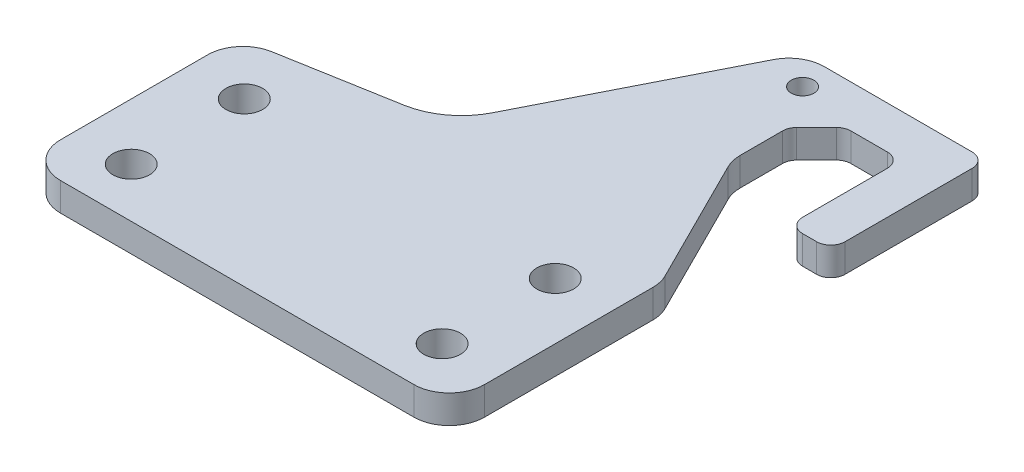
SolidWorks part; units mm, degrees
material "Thornel Mat VMA"
ref_plane "Front" through (0, 0, 0) normal (0, 0, 1) x (1, 0, 0)
ref_plane "Top" through (0, 0, 0) normal (0, 1, 0) x (1, 0, 0)
ref_plane "Right" through (0, 0, 0) normal (1, 0, 0) x (0, 0, -1)
sketch "草图1" plane through (0, 0, 0) normal (0, 1, 0) x (1, 0, 0)
  line L0 (0, 0) -> (0, 59.5856) construction
  line L1 (-30, -15) -> (30, -15)
  line L2 (-30, -15) -> (-30, 15)
  line L4 (30, -15) -> (30, 15)
  line L5 (-30, -15) -> (30, 15) construction
  line L6 (-30, 15) -> (30, -15) construction
  line L7 (30, 15) -> (20, 35)
  line L8 (20, 35) -> (20, 43)
  line L9 (20, 43) -> (24, 47)
  line L10 (24, 47) -> (24, 53)
  line L11 (24, 53) -> (12, 53)
  line L13 (12, 53) -> (-5, 19.4082)
  line L14 (-5, 19.4082) -> (-30, 15)
  point P0 (0, 0)
  dimension "D1" = 30
  dimension "D2" = 60
  dimension "D3" = 20
  dimension "D4" = 8
  dimension "D5" = 8
  dimension "D6" = 4
  dimension "D7" = 135
  dimension "D8" = 20
  dimension "D9" = 6
  dimension "D10" = 100
  dimension "D11" = 25
extrude "凸台-拉伸1" add sketch "草图1" along normal blind 4
fillet "圆角1" radius 10 1 edges at (-5, 2, -19.4082)
fillet "圆角2" radius 5 6 edges at (12, 2, -53) (20, 2, -35) (30, 2, -15) (30, 2, 15) (-30, 2, 15) (-30, 2, -15)
sketch "草图2" plane through (0, 4, 0) normal (0, 1, 0) x (1, 0, 0)
  line L0 (-30, 10.8045) -> (-30, -10) construction
  line L1 (-25, -15) -> (25, -15) construction
  line L2 (0, 0) -> (0, 22.3735) construction
  line L4 (0, 0) -> (-17.4119, 0) construction
  circle A0 centre (-22, 8) radius 2.6
  circle A1 centre (22, 8) radius 2.6
  circle A2 centre (22, -8) radius 2.6
  circle A3 centre (-22, -8) radius 2.6
  dimension "D1" = 5.2
  dimension "D2" = 8
  dimension "D3" = 23
extrude "切除-拉伸1" cut sketch "草图2" against normal through all
sketch "草图3" plane through (0, 0, 0) normal (0, -1, 0) x (1, 0, 0)
  line L0 (24, -53) -> (15.0734, -53) construction
  line L1 (20, -36.1803) -> (20, -43) construction
  circle A0 centre (16, -49) radius 1.6
  dimension "D1" = 3.2
  dimension "D2" = 4
  dimension "D3" = 4
extrude "切除-拉伸2" cut sketch "草图3" against normal through all
sketch "草图4" plane through (0, 4, 0) normal (0, 1, 0) x (1, 0, 0)
  line L0 (24, 47) -> (32, 47)
  line L1 (32, 47) -> (32, 31)
  line L2 (32, 31) -> (38, 31)
  line L3 (38, 31) -> (38, 53)
  line L4 (38, 53) -> (24, 53)
  line L5 (24, 53) -> (24, 47)
  dimension "D1" = 14
  dimension "D2" = 6
  dimension "D3" = 22
extrude "凸台-拉伸2" add sketch "草图4" against normal blind 4
fillet "圆角3" radius 2 6 edges at (20, 2, -43) (24, 2, -47) (32, 2, -47) (32, 2, -31) (38, 2, -53) (38, 2, -31)
